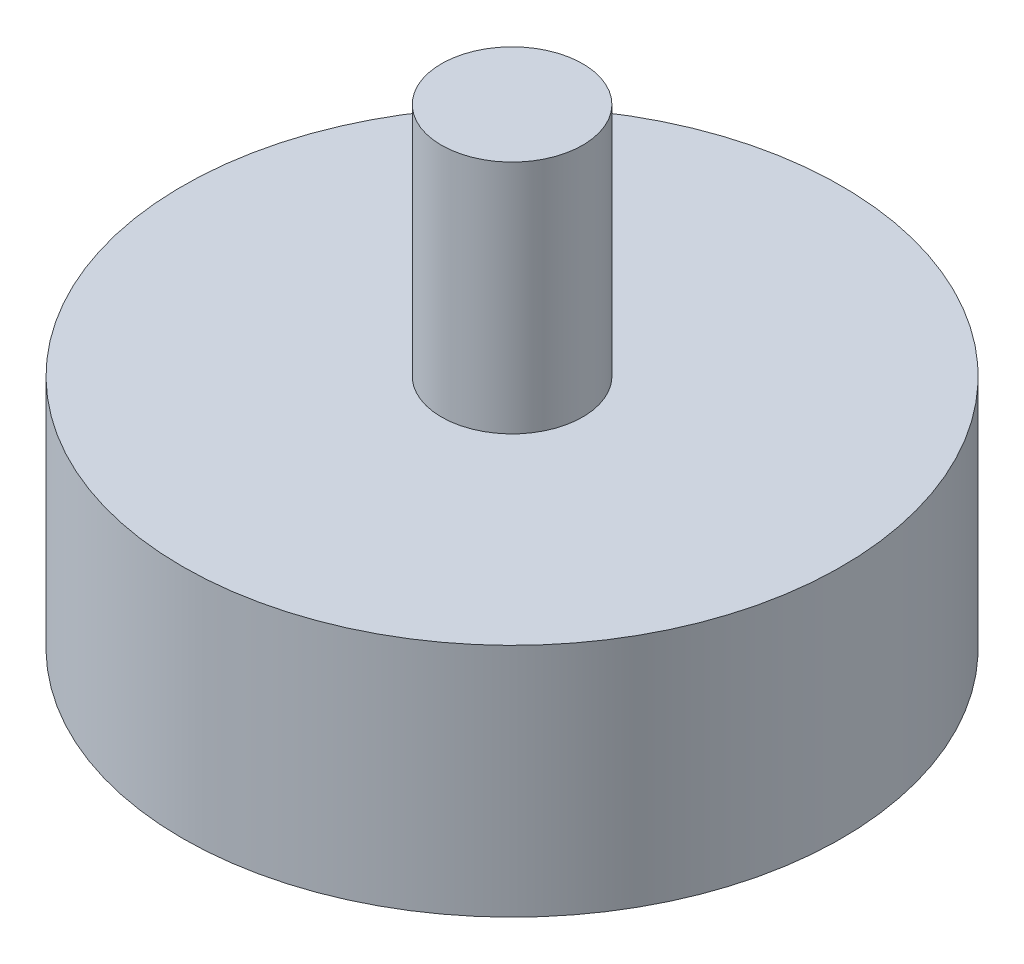
SolidWorks part; units mm, degrees
material "1023 Carbon Steel Sheet (SS)"
ref_plane "Front" through (0, 0, 0) normal (0, 0, 1) x (1, 0, 0)
ref_plane "Top" through (0, 0, 0) normal (0, 1, 0) x (1, 0, 0)
ref_plane "Right" through (0, 0, 0) normal (1, 0, 0) x (0, 0, -1)
sketch "Sketch1" plane through (0, 0, 0) normal (0, 1, 0) x (1, 0, 0)
  circle A0 centre (0, 0) radius 70
  circle A1 centre (0, 0) radius 120
  dimension "D1" = 240
  dimension "D2" = 50
extrude "Boss-Extrude1" add sketch "Sketch1" along normal blind 50 contours A0
sketch "Sketch2" plane through (0, 50, 0) normal (0, 1, 0) x (1, 0, 0)
  circle A0 centre (0, 0) radius 15
  dimension "D1" = 30
extrude "Boss-Extrude2" add sketch "Sketch2" along normal blind 50
sketch "Sketch3" plane through (0, 0, 0) normal (0, -1, 0) x (1, 0, 0)
  line L12 (-16.1921, 11.1149) -> (27.5408, 58.877)
  line L13 (27.5408, 58.877) -> (10.1116, 18.8649)
  line L14 (10.1116, 18.8649) -> (21.8812, 18.8649)
  line L15 (21.8812, 18.8649) -> (0, -11.1149)
  line L16 (0, -11.1149) -> (16.1921, -11.1149)
  line L17 (16.1921, -11.1149) -> (-27.5408, -58.877)
  line L18 (-27.5408, -58.877) -> (-8.3885, -16.5041)
  line L19 (-8.3885, -16.5041) -> (-20.1581, -16.5041)
  line L20 (-20.1581, -16.5041) -> (0, 11.1149)
  line L21 (0, 11.1149) -> (-16.1921, 11.1149)
  line L22 (0, 11.1149) -> (0, 0) construction
  line L23 (0, 0) -> (0, -11.1149) construction
  circle A0 centre (0, 0) radius 70 construction
  dimension "D1" = 16.1921
  dimension "D2" = 5
  dimension "D3" = 47.522
  dimension "D4" = 11.1149
  dimension "D5" = 34.1929
  dimension "D6" = 46.5003
  dimension "D7" = 11.7696
  dimension "D8" = 43.6434
extrude "Cut-Extrude1" cut sketch "Sketch3" against normal blind 5
